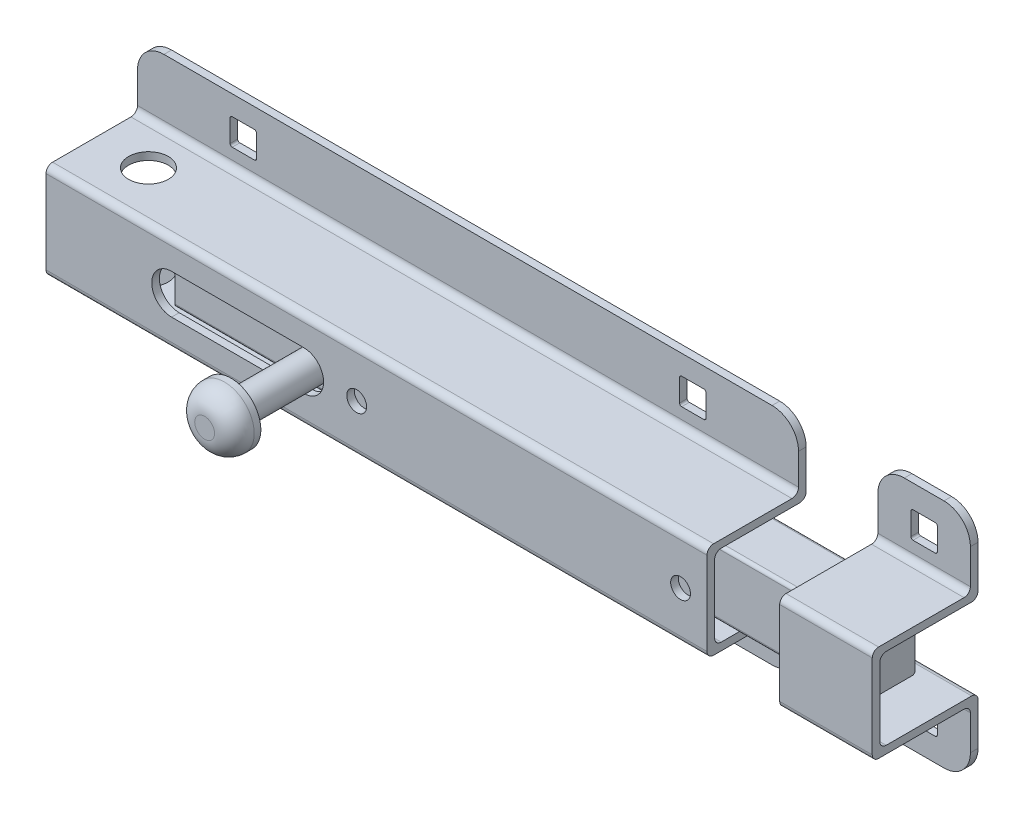
SolidWorks part; units mm, degrees
ref_plane "Front Plane" through (0, 0, 0) normal (0, 0, 1) x (1, 0, 0)
ref_plane "Top Plane" through (0, 0, 0) normal (0, 1, 0) x (1, 0, 0)
ref_plane "Right Plane" through (0, 0, 0) normal (1, 0, 0) x (0, 0, -1)
sketch "Sketch1" plane through (0, 0, 0) normal (0, 1, 0) x (1, 0, 0)
  line L0 (-79.375, 0) -> (79.375, 0) construction
  line L1 (0, 23.8125) -> (0, -23.8125) construction
  line L2 (79.375, 0) -> (111.125, 0) construction
  line L3 (98.425, 0) -> (120.65, 0) construction
  line L4 (165.1, 28.575) -> (167.4812, 28.575) construction
  line L5 (109.5375, 23.8125) -> (109.5375, -1.5875) construction
  line L6 (166.2906, 58.7375) -> (166.2906, -1.5875) construction
  line L7 (-66.675, 16.6688) -> (-66.675, 7.1438) construction
  point P4 (0, 0)
  point P8 (0, 0)
  point P13 (0, 5.5563)
  point P16 (109.5375, 0)
  point P19 (166.2906, 28.575)
  point P21 (0, 18.2563)
  point P24 (-66.675, 11.9063)
  dimension "D1" = 2.3813
  dimension "D2" = 12.7
  dimension "D3" = 44.45
  dimension "D4" = 12.7
  dimension "D5" = 6.35
  dimension "D6" = 25.4
sketch "Sketch2" plane through (0, 0, 0) normal (0, 0, 1) x (1, 0, 0)
  line L0 (0, 26.9875) -> (0, -26.9875) construction
  line L1 (109.5375, 27.7812) -> (109.5375, -27.7813) construction
  line L3 (166.2906, 19.05) -> (166.2906, -19.05) construction
  line L5 (0, 7.9375) -> (0, -7.9375) construction
  point P4 (0, 0)
  point P8 (109.5375, 0)
  point P12 (166.2906, 0)
  point P16 (0, 0)
  dimension "Edge Mount SP Height" = 38.1
  dimension "Surface Mount SP Height" = 55.5625
  dimension "Height" = 53.975
  dimension "Bolt Width" = 15.875
sketch "Sketch4" plane through (0, 0, 0) normal (1, 0, 0) x (0, 0, -1)
  line L0 (11.9062, 7.9375) -> (11.9063, 9.7663) construction
  line L1 (5.5563, -7.9375) -> (18.2563, -7.9375) construction
  line L2 (5.5563, -7.9375) -> (5.5562, 7.9375) construction
  line L3 (5.5562, 7.9375) -> (18.2563, 7.9375) construction
  line L4 (18.2563, -7.9375) -> (18.2563, 7.9375) construction
  line L5 (5.5563, 0) -> (1.8288, 0) construction
  line L6 (23.8125, 0) -> (-23.8125, 0) construction
  line L8 (18.2563, 0) -> (21.9837, 0) construction
  line L9 (1.8288, 0) -> (0, 0)
  line L10 (0, 0) -> (0, 10.0076)
  line L11 (1.5875, 11.5951) -> (20.3962, 11.5951)
  line L12 (21.9837, 13.1826) -> (21.9837, 26.9875)
  line L13 (21.9837, 26.9875) -> (23.8125, 26.9875)
  line L14 (23.8125, 26.9875) -> (23.8125, 11.3538)
  line L15 (22.225, 9.7663) -> (3.4163, 9.7663)
  line L16 (1.8288, 8.1788) -> (1.8288, 0)
  line L17 (11.9063, 9.7663) -> (11.9063, 11.5951) construction
  arc A0 (23.8125, 11.3538) -> (22.225, 9.7663) centre (22.225, 11.3538) cw
  arc A1 (20.3962, 11.5951) -> (21.9837, 13.1826) centre (20.3962, 13.1826) ccw
  arc A2 (0, 10.0076) -> (1.5875, 11.5951) centre (1.5875, 10.0076) cw
  arc A3 (3.4163, 9.7663) -> (1.8288, 8.1788) centre (3.4163, 8.1788) ccw
  point P4 (5.5563, 0)
  point P7 (18.2563, 0)
  dimension "D2" = 1.5875
  dimension "D1" = 1.8288
  dimension "D3" = 1.8288
extrude "Boss-Extrude1" add sketch "Sketch4" against normal up to vertex (79.375 mm away) and the other way up to vertex (79.375 mm away) up to point (-79.375, 0, 0) other way up to point (79.375, 0, 0)
mirror "Mirror1" about plane through (0, 0, 0) normal (0, 1, 0) of "Boss-Extrude1"
fillet "Fillet1" radius 6.35 4 edges at (-79.375, 26.9875, -22.8981) (79.375, -26.9875, -22.8981) (-79.375, -26.9875, -22.8981) (79.375, 26.9875, -22.8981)
sketch "Sketch5" plane through (0, 0, 0) normal (0, 0, 1) x (1, 0, 0)
  line L0 (-49.2125, 0) -> (-17.4625, 0) construction
  line L1 (-79.375, 0) -> (79.375, 0) construction
  line L2 (-49.2125, 4.7625) -> (-17.4625, 4.7625)
  line L3 (-49.2125, -4.7625) -> (-17.4625, -4.7625)
  arc A0 (-49.2125, 4.7625) -> (-49.2125, -4.7625) centre (-49.2125, 0) ccw
  arc A1 (-17.4625, -4.7625) -> (-17.4625, 4.7625) centre (-17.4625, 0) ccw
  circle A2 centre (73.025, 0) radius 2.3813
  circle A3 centre (-4.7625, 0) radius 2.3813
  point P4 (-33.3375, 0)
  dimension "D5" = 4.7625
  dimension "D1" = 31.75
  dimension "D2" = 9.525
  dimension "D3" = 165.1
  dimension "D4" = 4.7625
  dimension "D6" = 6.35
extrude "Cut-Extrude1" cut sketch "Sketch5" against normal up to next
sketch "Sketch6" plane through (0, -11.5951, 0) normal (0, -1, 0) x (1, 0, 0)
  circle A0 centre (-66.675, -11.9063) radius 4.7625
extrude "Cut-Extrude2" cut sketch "Sketch6" against normal through all
sketch "Sketch7" plane through (0, 0, -21.9837) normal (0, 0, 1) x (1, 0, 0)
  line L0 (0, 26.9875) -> (0, -26.9875) construction
  line L1 (-53.975, 19.05) -> (53.975, 19.05) construction
  line L2 (-53.975, 19.05) -> (-53.975, -19.05) construction
  line L3 (-53.975, -19.05) -> (53.975, -19.05) construction
  line L4 (53.975, 19.05) -> (53.975, -19.05) construction
  line L5 (79.375, 0) -> (111.125, 0) construction
  line L7 (-56.642, 22.225) -> (-51.308, 22.225)
  line L8 (-57.15, 21.717) -> (-57.15, 16.383)
  line L9 (-56.642, 15.875) -> (-51.308, 15.875)
  line L10 (-50.8, 21.717) -> (-50.8, 16.383)
  line L11 (-57.15, 22.225) -> (-50.8, 15.875) construction
  line L12 (-57.15, 15.875) -> (-50.8, 22.225) construction
  line L13 (51.308, 22.225) -> (56.642, 22.225)
  line L14 (50.8, 21.717) -> (50.8, 16.383)
  line L15 (51.308, 15.875) -> (56.642, 15.875)
  line L16 (57.15, 21.717) -> (57.15, 16.383)
  line L17 (50.8, 22.225) -> (57.15, 15.875) construction
  line L18 (50.8, 15.875) -> (57.15, 22.225) construction
  line L19 (51.308, -15.875) -> (56.642, -15.875)
  line L20 (50.8, -16.383) -> (50.8, -21.717)
  line L21 (51.308, -22.225) -> (56.642, -22.225)
  line L22 (57.15, -16.383) -> (57.15, -21.717)
  line L23 (50.8, -15.875) -> (57.15, -22.225) construction
  line L24 (50.8, -22.225) -> (57.15, -15.875) construction
  line L25 (-56.642, -15.875) -> (-51.308, -15.875)
  line L26 (-57.15, -16.383) -> (-57.15, -21.717)
  line L27 (-56.642, -22.225) -> (-51.308, -22.225)
  line L28 (-50.8, -16.383) -> (-50.8, -21.717)
  line L29 (-57.15, -15.875) -> (-50.8, -22.225) construction
  line L30 (-57.15, -22.225) -> (-50.8, -15.875) construction
  arc A0 (-51.308, 15.875) -> (-50.8, 16.383) centre (-51.308, 16.383) ccw
  arc A1 (-57.15, 16.383) -> (-56.642, 15.875) centre (-56.642, 16.383) ccw
  arc A2 (-51.308, 22.225) -> (-50.8, 21.717) centre (-51.308, 21.717) cw
  arc A3 (-56.642, 22.225) -> (-57.15, 21.717) centre (-56.642, 21.717) ccw
  arc A4 (-51.308, -22.225) -> (-50.8, -21.717) centre (-51.308, -21.717) ccw
  arc A5 (-57.15, -21.717) -> (-56.642, -22.225) centre (-56.642, -21.717) ccw
  arc A6 (-51.308, -15.875) -> (-50.8, -16.383) centre (-51.308, -16.383) cw
  arc A7 (-56.642, -15.875) -> (-57.15, -16.383) centre (-56.642, -16.383) ccw
  arc A8 (56.642, -15.875) -> (57.15, -16.383) centre (56.642, -16.383) cw
  arc A9 (56.642, -22.225) -> (57.15, -21.717) centre (56.642, -21.717) ccw
  arc A10 (50.8, -21.717) -> (51.308, -22.225) centre (51.308, -21.717) ccw
  arc A11 (51.308, -15.875) -> (50.8, -16.383) centre (51.308, -16.383) ccw
  arc A12 (56.642, 22.225) -> (57.15, 21.717) centre (56.642, 21.717) cw
  arc A13 (56.642, 15.875) -> (57.15, 16.383) centre (56.642, 16.383) ccw
  arc A14 (50.8, 16.383) -> (51.308, 15.875) centre (51.308, 16.383) ccw
  arc A15 (51.308, 22.225) -> (50.8, 21.717) centre (51.308, 21.717) ccw
  point P4 (0, 19.05)
  point P7 (53.975, 0)
  dimension "D4" = 0.508
  dimension "D5" = 0.508
  dimension "D6" = 0.508
  dimension "D1" = 107.95
  dimension "D2" = 38.1
  dimension "D3" = 6.35
extrude "Cut-Extrude3" cut sketch "Sketch7" against normal through all
ref_plane "Plane1" through (111.125, 0, 0) normal (1, 0, 0) x (0, 0, -1)
sketch "Sketch8" plane through (111.125, 0, 0) normal (1, 0, 0) x (0, 0, -1)
  line L1 (6.3183, 7.9375) -> (17.4943, 7.9375)
  line L2 (5.5563, 7.1755) -> (5.5563, -7.1755)
  line L3 (6.3183, -7.9375) -> (17.4943, -7.9375)
  line L4 (18.2563, 7.1755) -> (18.2563, -7.1755)
  arc A0 (5.5563, -7.1755) -> (6.3183, -7.9375) centre (6.3183, -7.1755) ccw
  arc A1 (17.4943, -7.9375) -> (18.2563, -7.1755) centre (17.4943, -7.1755) ccw
  arc A2 (17.4943, 7.9375) -> (18.2563, 7.1755) centre (17.4943, 7.1755) cw
  arc A3 (6.3183, 7.9375) -> (5.5563, 7.1755) centre (6.3183, 7.1755) ccw
  point P4 (5.5563, 0)
  dimension "D1" = 0.762
extrude "Boss-Extrude2" add sketch "Sketch8" against normal blind 165.1 separate body
ref_axis "Axis1" through (-17.4625, 0, -65.2289) along (0, 0, 1)
sketch "Sketch12" plane through (0, 0, 0) normal (0, 1, 0) x (1, 0, 0)
  line L0 (-17.4625, 5.5563) -> (-17.4625, -23.8125)
  line L1 (-53.975, 5.5563) -> (111.125, 5.5563) construction
  line L2 (-17.4625, -23.8125) -> (-10.3187, -23.8125) construction
  line L3 (-10.3187, -23.8125) -> (-10.3187, -17.4625) construction
  line L4 (-10.3187, -17.4625) -> (-13.8906, -17.4625)
  line L5 (-13.8906, -17.4625) -> (-13.8906, 5.5563)
  line L6 (-13.8906, 5.5563) -> (-17.4625, 5.5563)
  line L7 (-17.4625, 65.2289) -> (-17.4625, -41.3802) construction
  line L8 (-17.4625, -23.8125) -> (-15.0812, -23.8125)
  line L9 (-10.3187, -19.05) -> (-10.3187, -17.4625)
  arc A1 (-15.0812, -23.8125) -> (-10.3187, -19.05) centre (-15.0812, -19.05) ccw
  dimension "D1" = 3.5719
  dimension "D2" = 7.1437
  dimension "D3" = 6.35
  dimension "D4" = 1.5875
revolve "Revolve1" add sketch "Sketch12" angle 360 about axis through (-17.4625, 0, -65.2289) along (0, 0, 1)
ref_plane "Plane2" through (109.5375, 0, 0) normal (1, 0, 0) x (0, 0, -1)
ref_plane "Plane3" through (166.2906, 0, 0) normal (1, 0, 0) x (0, 0, -1)
sketch "Sketch16" plane through (0, 0, 0) normal (0, 0, 1) x (1, 0, 0)
  line L0 (79.375, 7.9375) -> (-53.975, 7.9375)
  line L1 (-53.975, 7.9375) -> (-53.975, -7.9375)
  line L2 (-53.975, -7.9375) -> (79.375, -7.9375)
  line L3 (79.375, 10.0076) -> (79.375, -10.0076) construction
  line L4 (-53.975, 7.9375) -> (111.125, 7.9375) construction
  line L5 (-53.975, -7.9375) -> (111.125, -7.9375) construction
  arc A3 (-49.2125, 4.7625) -> (-49.2125, -4.7625) centre (-49.2125, 0) ccw construction
sketch "Sketch13" plane through (109.5375, 0, 0) normal (1, 0, 0) x (0, 0, -1)
  line L0 (-1.5875, 0) -> (0.2413, 0)
  line L1 (0.2413, 0) -> (0.2413, 8.2423)
  line L2 (1.7653, 9.7663) -> (22.2885, 9.7663)
  line L3 (23.8125, 11.2903) -> (23.8125, 27.7812)
  line L4 (23.8125, 27.7812) -> (21.9837, 27.7812)
  line L5 (21.9837, 27.7812) -> (21.9837, 13.1191)
  line L6 (20.4597, 11.5951) -> (-0.0635, 11.5951)
  line L7 (-1.5875, 10.0711) -> (-1.5875, 0)
  line L8 (12.0269, 9.7663) -> (12.0269, 11.5951)
  line L9 (1.5875, 11.5951) -> (20.3962, 11.5951) construction
  arc A0 (22.2885, 9.7663) -> (23.8125, 11.2903) centre (22.2885, 11.2903) ccw
  arc A1 (21.9837, 13.1191) -> (20.4597, 11.5951) centre (20.4597, 13.1191) cw
  arc A2 (0.2413, 8.2423) -> (1.7653, 9.7663) centre (1.7653, 8.2423) cw
  arc A3 (-0.0635, 11.5951) -> (-1.5875, 10.0711) centre (-0.0635, 10.0711) ccw
  dimension "D2" = 1.524
  dimension "D1" = 1.8288
extrude "Boss-Extrude3" add sketch "Sketch13" against normal up to vertex (11.1125 mm away) and the other way up to vertex (11.1125 mm away) separate body contours L2 A0 L3 L4 L5 A1 L6 A3 L7 L0 L1 A2 up to point (98.425, 0, 0) other way up to point (120.65, 0, 0)
mirror "Mirror5" about plane through (0, 0, 0) normal (0, 1, 0) of "Boss-Extrude3"
fillet "Fillet3" radius 6.35 4 edges at (120.65, -27.7812, -22.8981) (98.425, -27.7812, -22.8981) (120.65, 27.7812, -22.8981) (98.425, 27.7812, -22.8981)
sketch "Sketch14" plane through (0, 0, -21.9837) normal (0, 0, 1) x (1, 0, 0)
  line L1 (106.8705, 22.225) -> (112.2045, 22.225)
  line L2 (106.3625, 21.717) -> (106.3625, 16.383)
  line L3 (106.8705, 15.875) -> (112.2045, 15.875)
  line L4 (112.7125, 21.717) -> (112.7125, 16.383)
  line L5 (106.8705, -15.875) -> (112.2045, -15.875)
  line L6 (106.3625, -16.383) -> (106.3625, -21.717)
  line L7 (106.8705, -22.225) -> (112.2045, -22.225)
  line L8 (112.7125, -16.383) -> (112.7125, -21.717)
  line L10 (109.5375, 27.7812) -> (109.5375, -27.7813) construction
  line L11 (51.308, -22.225) -> (56.642, -22.225) construction
  line L12 (56.642, -15.875) -> (51.308, -15.875) construction
  line L13 (51.308, 15.875) -> (56.642, 15.875) construction
  arc A0 (112.2045, -22.225) -> (112.7125, -21.717) centre (112.2045, -21.717) ccw
  arc A1 (106.3625, -21.717) -> (106.8705, -22.225) centre (106.8705, -21.717) ccw
  arc A2 (112.2045, -15.875) -> (112.7125, -16.383) centre (112.2045, -16.383) cw
  arc A3 (106.8705, -15.875) -> (106.3625, -16.383) centre (106.8705, -16.383) ccw
  arc A4 (112.2045, 22.225) -> (112.7125, 21.717) centre (112.2045, 21.717) cw
  arc A5 (112.2045, 15.875) -> (112.7125, 16.383) centre (112.2045, 16.383) ccw
  arc A6 (106.3625, 16.383) -> (106.8705, 15.875) centre (106.8705, 16.383) ccw
  arc A7 (106.8705, 22.225) -> (106.3625, 21.717) centre (106.8705, 21.717) ccw
  point P24 (109.5375, -15.875)
  point P27 (109.5375, 15.875)
  dimension "D1" = 0.508
extrude "Cut-Extrude4" cut sketch "Sketch14" against normal through all
sketch "Sketch15" [suppressed] plane through (229.7906, 0, 0) normal (1, 0, 0) x (0, 0, -1)
  line L0 (5.1337, 19.05) -> (57.9437, 19.05)
  line L1 (58.7375, 19.05) -> (-1.5875, 19.05) construction
  line L2 (58.7375, 18.2563) -> (58.7375, -18.2563)
  line L3 (58.7375, -19.05) -> (-1.5875, -19.05) construction
  line L4 (-1.5875, 19.05) -> (-1.5875, -19.05) construction
  line L5 (5.1337, -19.05) -> (57.9438, -19.05)
  line L6 (58.7375, 0) -> (-1.5875, 0) construction
  line L7 (18.542, 8.7312) -> (5.2705, 8.7312)
  line L8 (19.05, 8.2232) -> (19.05, -8.2232)
  line L9 (18.542, -8.7312) -> (5.2705, -8.7313)
  line L10 (4.7625, 8.2232) -> (4.7625, -8.2232)
  line L11 (19.05, 8.7312) -> (4.7625, -8.7313) construction
  line L12 (19.05, -8.7312) -> (4.7625, 8.7312) construction
  line L13 (5.5562, 7.9375) -> (18.2563, 7.9375) construction
  line L14 (5.5563, -7.9375) -> (5.5562, 7.9375) construction
  line L15 (18.2563, -7.9375) -> (18.2563, 7.9375) construction
  line L16 (49.2125, 10.3187) -> (47.625, -10.3187) construction
  arc A0 (2.2605, 17.2261) -> (2.2605, -17.2261) centre (38.8938, 0) ccw
  circle A1 centre (49.2125, 10.3187) radius 3.175
  circle A2 centre (47.625, -10.3187) radius 3.175
  arc A3 (19.05, -8.2232) -> (18.542, -8.7312) centre (18.542, -8.2232) cw
  arc A4 (5.2705, -8.7313) -> (4.7625, -8.2232) centre (5.2705, -8.2233) cw
  arc A5 (18.542, 8.7312) -> (19.05, 8.2232) centre (18.542, 8.2233) cw
  arc A6 (5.2705, 8.7312) -> (4.7625, 8.2232) centre (5.2705, 8.2233) ccw
  arc A7 (2.2605, -17.2261) -> (5.1337, -19.05) centre (5.1337, -15.875) ccw
  arc A8 (2.2605, 17.2261) -> (5.1337, 19.05) centre (5.1337, 15.875) cw
  arc A9 (58.7375, -18.2563) -> (57.9438, -19.05) centre (57.9438, -18.2563) cw
  arc A10 (57.9437, 19.05) -> (58.7375, 18.2563) centre (57.9437, 18.2563) cw
  point P4 (58.7375, 0)
  point P11 (11.9063, 0)
  point P40 (48.4187, 0)
  point P43 (3.175, -19.05)
  point P46 (3.175, 19.05)
  dimension "D2" = 6.35
  dimension "D3" = 6.35
  dimension "D7" = 0.508
  dimension "D11" = 3.175
  dimension "D12" = 0.7937
  dimension "D1" = 4.7625
  dimension "D4" = 0.7937
  dimension "D5" = 0.7937
  dimension "D6" = 0.7937
  dimension "D8" = 20.6375
  dimension "D9" = 1.5875
  dimension "D10" = 11.1125
extrude "Boss-Extrude4" [suppressed] add sketch "Sketch15" against normal up to vertex and the other way up to vertex separate body
chamfer "Chamfer1" [suppressed] distance 0.508 angle 45
equation "\"D5@Sketch1\"=\"Bolt Thickness@Sketch1\"/2"
equation "\"D1@Sketch5\"=\"Bolt Projection@Sketch1\""
